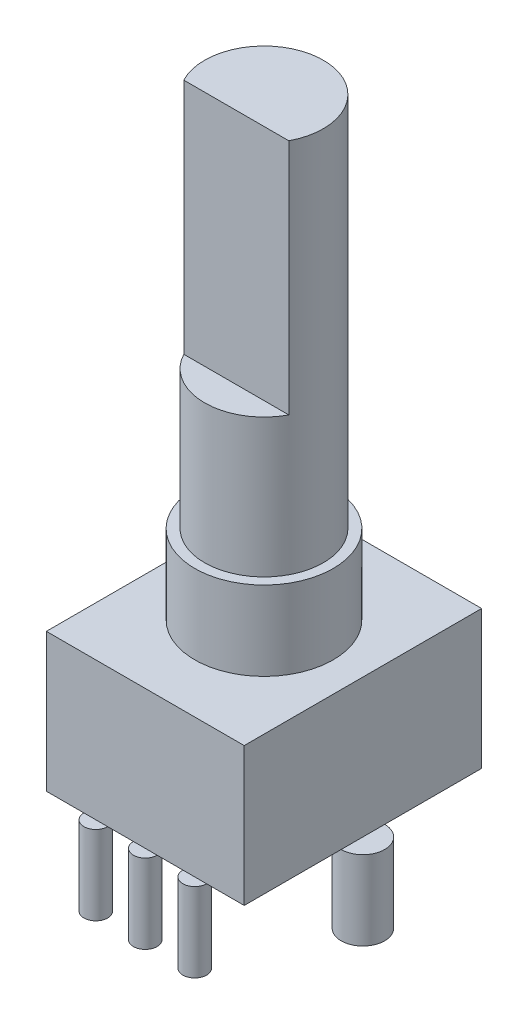
SolidWorks part; units mm, degrees
ref_plane "Front Plane" through (0, 0, 0) normal (0, 0, 1) x (1, 0, 0)
ref_plane "Top Plane" through (0, 0, 0) normal (0, 1, 0) x (1, 0, 0)
ref_plane "Right Plane" through (0, 0, 0) normal (1, 0, 0) x (0, 0, -1)
sketch "Sketch1" plane through (0, 0, 0) normal (0, 1, 0) x (1, 0, 0)
  circle A0 centre (0, 0) radius 3
  dimension "D1" = 6
extrude "Boss-Extrude1" add sketch "Sketch1" along normal blind 7
sketch "Sketch2" plane through (0, 7, 0) normal (0, 1, 0) x (1, 0, 0)
  line L0 (-2.6533, -1.4) -> (2.6533, -1.4)
  circle A1 centre (0, 0) radius 3
  arc A2 (2.6533, -1.4) -> (-2.6533, -1.4) centre (0, 0) ccw
  dimension "D2" = 4.4
  dimension "D1" = 0
extrude "Boss-Extrude2" add sketch "Sketch2" along normal blind 12
sketch "Sketch3" plane through (0, 0, 0) normal (0, -1, 0) x (1, 0, 0)
  circle A2 centre (0, 0) radius 3.5
  circle A3 centre (0, 0) radius 3.5
  dimension "D1" = 0.5
extrude "Boss-Extrude3" add sketch "Sketch3" along normal blind 4
sketch "Sketch4" plane through (0, -4, 0) normal (0, -1, 0) x (1, 0, 0)
  line L0 (-5, -6) -> (5, 6) construction
  line L1 (-5, -6) -> (5, -6)
  line L2 (-5, -6) -> (-5, 6)
  line L3 (-5, 6) -> (5, 6)
  line L4 (5, -6) -> (5, 6)
  dimension "D1" = 10
  dimension "D2" = 12
extrude "Boss-Extrude4" add sketch "Sketch4" along normal blind 7
sketch "Sketch5" plane through (0, -11, 0) normal (0, -1, 0) x (1, 0, 0)
  line L0 (5.5, 0) -> (-5.5, 0) construction
  line L1 (5, -6) -> (5, 6) construction
  circle A0 centre (-5.0012, 0) radius 1.1
  circle A1 centre (5, 0) radius 1.1
  dimension "D1" = 2.2
extrude "Boss-Extrude5" add sketch "Sketch5" along normal blind 4
sketch "Sketch6" plane through (0, -11, 0) normal (0, -1, 0) x (1, 0, 0)
  line L0 (5, 6) -> (-5, 6) construction
  line L1 (-2.5, 6) -> (0, 6) construction
  line L2 (0, 6) -> (2.5, 6) construction
  circle A0 centre (0, 6) radius 0.6
  circle A1 centre (2.5, 6) radius 0.6
  circle A2 centre (-2.5, 6) radius 0.6
  dimension "D1" = 1.2
  dimension "D2" = 2.5
extrude "Boss-Extrude6" add sketch "Sketch6" along normal blind 4
